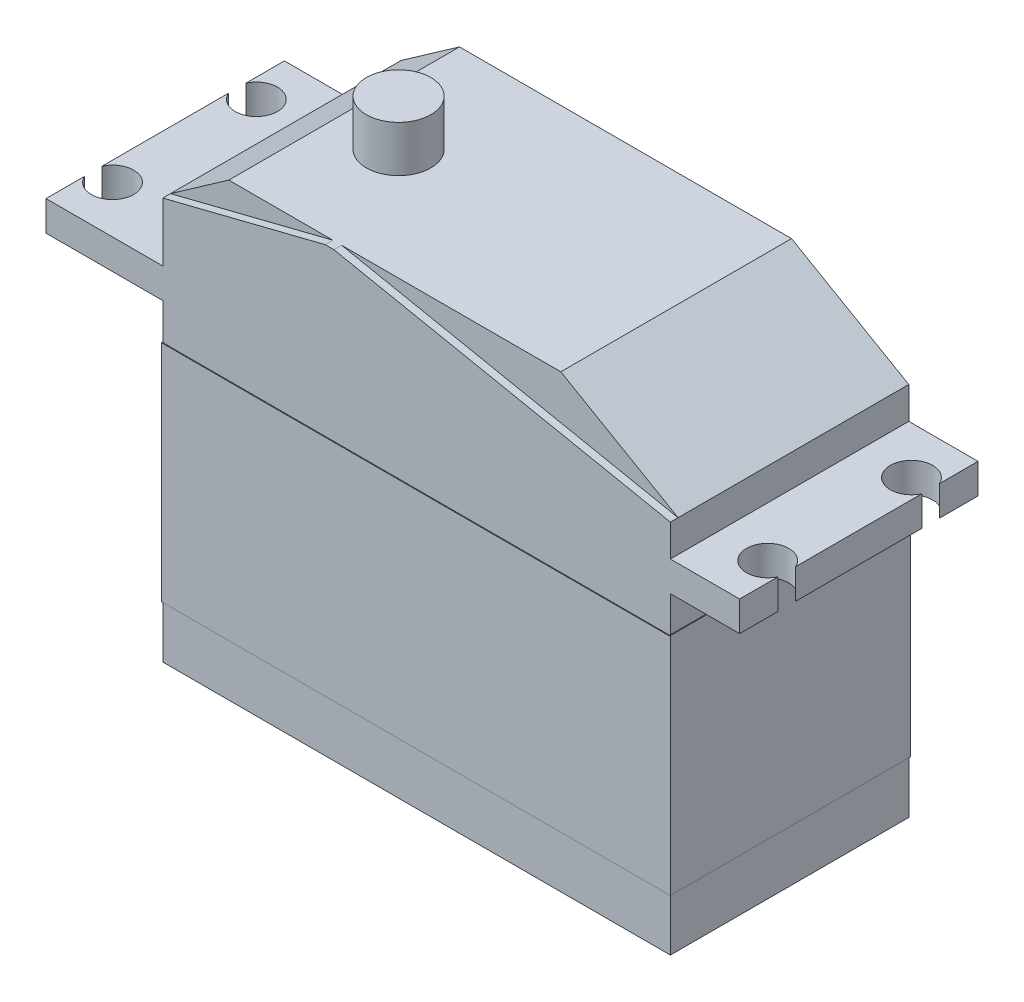
SolidWorks part; units mm, degrees
ref_plane "Front Plane" through (0, 0, 0) normal (0, 0, 1) x (1, 0, 0)
ref_plane "Top Plane" through (0, 0, 0) normal (0, 1, 0) x (1, 0, 0)
ref_plane "Right Plane" through (0, 0, 0) normal (1, 0, 0) x (0, 0, -1)
sketch "Sketch2" plane through (0, 0, 0) normal (0, 1, 0) x (1, 0, 0)
  line L1 (-33, -15.5) -> (33, -15.5)
  line L2 (-33, -15.5) -> (-33, 15.5)
  line L3 (-33, 15.5) -> (33, 15.5)
  line L4 (33, -15.5) -> (33, 15.5)
  line L5 (-33, -15.5) -> (33, 15.5) construction
  line L6 (-33, 15.5) -> (33, -15.5) construction
  point P0 (0, 0)
  dimension "D1" = 66
  dimension "D2" = 31
extrude "Boss-Extrude1" add sketch "Sketch2" along normal blind 44.6
sketch "Sketch4" plane through (33, 0, 0) normal (1, 0, 0) x (0, 0, -1)
  line L0 (15.5, 44.6) -> (15.5, 0) construction
  line L1 (-15.5, 44.6) -> (15.5, 44.6)
  line L2 (-15.5, 44.6) -> (-15.5, 40.7)
  line L3 (-15.5, 40.7) -> (15.5, 40.7)
  line L4 (15.5, 44.6) -> (15.5, 40.7)
  dimension "D1" = 3.9
extrude "Boss-Extrude2" add sketch "Sketch4" along normal blind 9
sketch "Sketch6" plane through (0, 44.6, 0) normal (0, 1, 0) x (1, 0, 0)
  line L0 (-33, -15.5) -> (42, -15.5) construction
  line L2 (0, 0) -> (44.6202, 0) construction
  line L4 (42, 15.5) -> (42, -15.5) construction
  circle A0 centre (39.5, -9.35) radius 2.75
  circle A1 centre (39.5, 9.35) radius 2.75
  dimension "D1" = 5.5
  dimension "D3" = 2.5
  dimension "D2" = 6.15
extrude "Cut-Extrude3" cut sketch "Sketch6" against normal through all
sketch "Sketch7" plane through (0, 44.6, 0) normal (0, 1, 0) x (1, 0, 0)
  line L0 (0, 0) -> (-39.316, 0) construction
  line L1 (-33, 15.5) -> (-48.1861, 15.5)
  line L2 (-33, 15.5) -> (-33, -15.5)
  line L3 (-33, -15.5) -> (-48.1861, -15.5)
  line L4 (-48.1861, 15.5) -> (-48.1861, 10.4956)
  line L5 (-48.1861, 8.2044) -> (-48.1861, -8.2044)
  line L6 (-48.1861, -10.4956) -> (-48.1861, -15.5)
  line L7 (-33, -15.5) -> (42, -15.5) construction
  arc A0 (-48.1861, -10.4956) -> (-48.1861, -8.2044) centre (-45.6861, -9.35) ccw
  arc A2 (-48.1861, 10.4956) -> (-48.1861, 8.2044) centre (-45.6861, 9.35) cw
  dimension "D1" = 5.5
  dimension "D2" = 2.5
  dimension "D3" = 6.15
extrude "Boss-Extrude4" add sketch "Sketch7" against normal blind 3.9
sketch "Sketch8" plane through (0, 44.6, 0) normal (0, 1, 0) x (1, 0, 0)
  line L1 (-33, -15.5) -> (33, -15.5)
  line L2 (-33, -15.5) -> (-33, 15.5)
  line L3 (-33, 15.5) -> (33, 15.5)
  line L4 (33, -15.5) -> (33, 15.5)
  line L5 (-33, -15.5) -> (33, 15.5) construction
  line L6 (-33, 15.5) -> (33, -15.5) construction
  point P0 (0, 0)
extrude "Boss-Extrude5" add sketch "Sketch8" along normal blind 12.96
sketch "Sketch9" plane through (0, 0, 15.5) normal (0, 0, 1) x (1, 0, 0)
  line L0 (-25.418, 57.56) -> (-33, 52.251)
  line L1 (-33, 57.56) -> (33, 57.56) construction
  line L2 (-33, 57.56) -> (-33, 44.6) construction
  line L4 (-25.418, 57.56) -> (-33, 57.56)
  line L5 (-33, 57.56) -> (-33, 52.251)
extrude "Cut-Extrude7" cut sketch "Sketch9" against normal through all
sketch "Sketch10" plane through (0, 0, 15.5) normal (0, 0, 1) x (1, 0, 0)
  line L0 (17.7519, 57.56) -> (33, 48.7565)
  line L1 (-25.418, 57.56) -> (33, 57.56) construction
  line L2 (33, 57.56) -> (33, 44.6) construction
  line L4 (17.7519, 57.56) -> (33, 57.56)
  line L5 (33, 57.56) -> (33, 48.7565)
extrude "Cut-Extrude8" cut sketch "Sketch10" against normal through all
sketch "Sketch11" plane through (0, 0, 15.5) normal (0, 0, 1) x (1, 0, 0)
  line L0 (-33, 52.251) -> (-11.8895, 57.56)
  line L1 (-25.418, 57.56) -> (17.7519, 57.56) construction
  line L2 (-11.8895, 57.56) -> (-25.418, 57.56)
  line L3 (-25.418, 57.56) -> (-33, 52.251)
  line L4 (33, 48.7565) -> (-10.7554, 57.56)
  line L5 (-10.7554, 57.56) -> (17.7519, 57.56)
  line L6 (17.7519, 57.56) -> (33, 48.7565)
extrude "Cut-Extrude9" cut sketch "Sketch11" against normal blind 1
sketch "Sketch12" plane through (0, 57.56, 0) normal (0, 1, 0) x (1, 0, 0)
  line L0 (-25.418, 15.5) -> (-25.418, -14.5) construction
  circle A0 centre (-17.8393, 0) radius 4.19
  dimension "D1" = 8.38
  dimension "D2" = 7.5787
extrude "Boss-Extrude6" add sketch "Sketch12" along normal blind 6
sketch "Sketch13" plane through (0, 0, -15.5) normal (0, 0, -1) x (-1, 0, 0)
  line L0 (-33, 40.7) -> (-33, 0) construction
  line L1 (-33, 36.0734) -> (33, 36.0734)
  line L2 (-33, 36.0734) -> (-33, 6.8075)
  line L3 (-33, 6.8075) -> (33, 6.8075)
  line L4 (33, 36.0734) -> (33, 6.8075)
  line L5 (33, 40.7) -> (33, 0) construction
extrude "Boss-Extrude7" add sketch "Sketch13" along normal blind 0.1
sketch "Sketch14" plane through (-33, 0, 0) normal (-1, 0, 0) x (0, 0, 1)
  line L0 (15.5, 40.7) -> (15.5, 0) construction
  line L1 (-15.6, 6.8075) -> (15.5, 6.8075)
  line L2 (-15.6, 6.8075) -> (-15.6, 35.9721)
  line L3 (-15.6, 35.9721) -> (15.5, 35.9721)
  line L4 (15.5, 6.8075) -> (15.5, 35.9721)
extrude "Boss-Extrude8" add sketch "Sketch14" along normal blind 0.1
sketch "Sketch15" plane through (0, 0, 15.5) normal (0, 0, 1) x (1, 0, 0)
  line L1 (-33.1, 35.9721) -> (33, 35.9721)
  line L2 (-33.1, 35.9721) -> (-33.1, 6.8075)
  line L3 (-33.1, 6.8075) -> (33, 6.8075)
  line L4 (33, 35.9721) -> (33, 6.8075)
extrude "Boss-Extrude9" add sketch "Sketch15" along normal blind 0.1
sketch "Sketch16" plane through (33, 0, 0) normal (1, 0, 0) x (0, 0, -1)
  line L1 (15.6, 36.0734) -> (-15.6, 36.0734)
  line L2 (15.6, 36.0734) -> (15.6, 6.8075)
  line L3 (15.6, 6.8075) -> (-15.6, 6.8075)
  line L4 (-15.6, 36.0734) -> (-15.6, 6.8075)
extrude "Boss-Extrude10" add sketch "Sketch16" along normal blind 0.1
